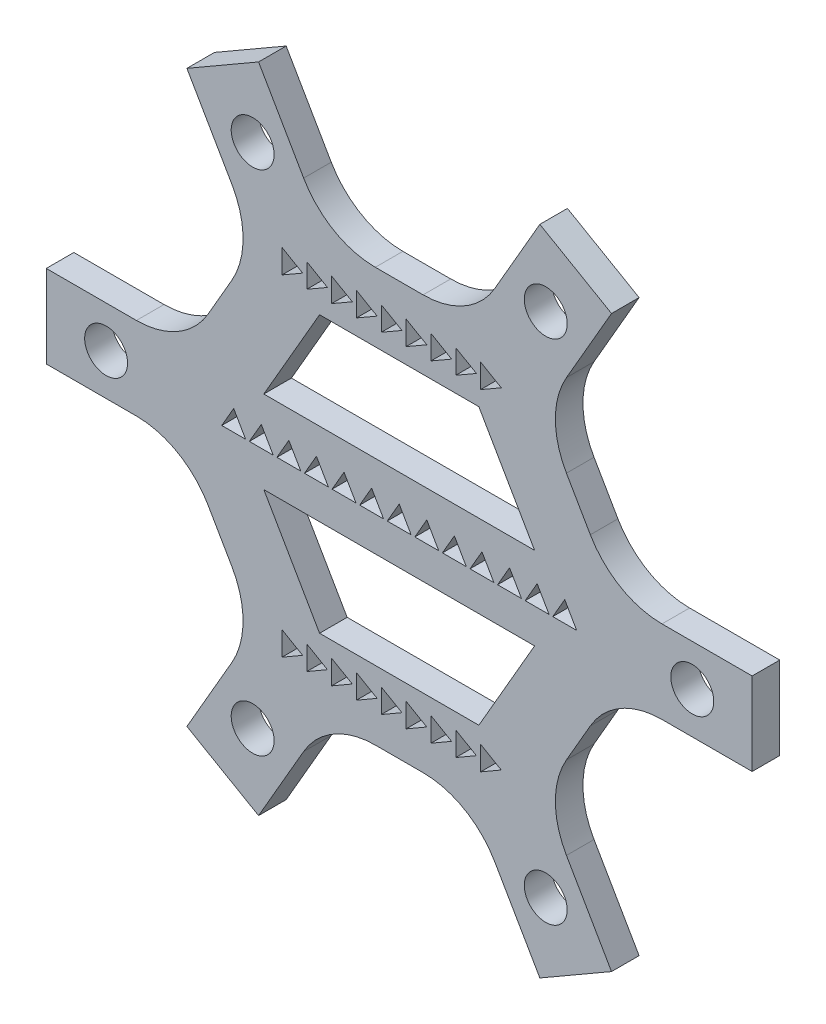
SolidWorks part; units mm, degrees
ref_plane "Front Plane" through (0, 0, 0) normal (0, 0, 1) x (1, 0, 0)
ref_plane "Top Plane" through (0, 0, 0) normal (0, 1, 0) x (1, 0, 0)
ref_plane "Right Plane" through (0, 0, 0) normal (1, 0, 0) x (0, 0, -1)
sketch "Sketch1" plane through (0, 0, 0) normal (0, 0, 1) x (1, 0, 0)
  line L0 (-49.0748, 15) -> (49.0748, 15)
  line L1 (69.282, 30) -> (60.6218, 45)
  line L2 (8.6603, 75) -> (-8.6603, 75)
  line L3 (-60.6218, 45) -> (-69.282, 30)
  line L4 (-69.282, -30) -> (-60.6218, -45)
  line L5 (-8.6603, -75) -> (8.6603, -75)
  line L6 (60.6218, -45) -> (69.282, -30)
  line L7 (57.735, 0) -> (28.8675, 50)
  line L8 (28.8675, 50) -> (-28.8675, 50)
  line L9 (-28.8675, 50) -> (-57.735, 0)
  line L10 (-57.735, 0) -> (-28.8675, -50)
  line L11 (-28.8675, -50) -> (28.8675, -50)
  line L12 (28.8675, -50) -> (57.735, 0)
  line L13 (34.641, 90) -> (50.9808, 118.3013)
  line L14 (-49.0748, -15) -> (49.0748, -15)
  line L15 (60.6218, 75) -> (76.9615, 103.3013)
  line L16 (95.2628, 15) -> (127.9423, 15)
  line L17 (95.2628, -15) -> (127.9423, -15)
  line L18 (34.641, -90) -> (50.9808, -118.3013)
  line L19 (60.6218, -75) -> (76.9615, -103.3013)
  line L20 (-60.6218, -75) -> (-76.9615, -103.3013)
  line L21 (-34.641, -90) -> (-50.9808, -118.3013)
  line L22 (-34.641, 90) -> (-50.9808, 118.3013)
  line L23 (-60.6218, 75) -> (-76.9615, 103.3013)
  line L24 (-95.2628, -15) -> (-127.9423, -15)
  line L25 (-95.2628, 15) -> (-127.9423, 15)
  line L26 (50.9808, 118.3013) -> (76.9615, 103.3013)
  line L27 (127.9423, 15) -> (127.9423, -15)
  line L28 (76.9615, -103.3013) -> (50.9808, -118.3013)
  line L29 (-76.9615, 103.3013) -> (-50.9808, 118.3013)
  line L30 (-127.9423, 15) -> (-127.9423, -15)
  line L31 (-76.9615, -103.3013) -> (-50.9808, -118.3013)
  circle A0 centre (0, 0) radius 75 construction
  arc A7 (-69.282, -30) -> (-95.2628, -15) centre (-95.2628, -45) ccw
  arc A8 (-69.282, 30) -> (-95.2628, 15) centre (-95.2628, 45) cw
  arc A9 (-60.6218, -45) -> (-60.6218, -75) centre (-86.6025, -60) cw
  arc A10 (-8.6603, -75) -> (-34.641, -90) centre (-8.6603, -105) ccw
  arc A11 (69.282, 30) -> (95.2628, 15) centre (95.2628, 45) ccw
  arc A12 (60.6218, 45) -> (60.6218, 75) centre (86.6025, 60) cw
  arc A13 (8.6603, 75) -> (34.641, 90) centre (8.6603, 105) ccw
  arc A14 (69.282, -30) -> (95.2628, -15) centre (95.2628, -45) cw
  arc A15 (60.6218, -45) -> (60.6218, -75) centre (86.6025, -60) ccw
  arc A16 (8.6603, -75) -> (34.641, -90) centre (8.6603, -105) cw
  arc A17 (-8.6603, 75) -> (-34.641, 90) centre (-8.6603, 105) cw
  arc A18 (-60.6218, 45) -> (-60.6218, 75) centre (-86.6025, 60) ccw
  dimension "D1" = 30
  dimension "D2" = 30
  dimension "D3" = 30
  dimension "D4" = 30
  dimension "D5" = 30
extrude "Boss-Extrude2" add sketch "Sketch1" along normal blind 10 contours L10 L14 L12 L7 L0 L9 | A18 L3 A8 L25 L30 L24 A7 L4 A9 L20 L31 L21 A10 L5 A16 L18 L28 L19 A15 L6 A14 L17 L27 L16 A11 L1 A12 L15 L26 L13 A13 L2 A17 L22 L29 L23 L12 L11 L10 L9 L8 L7
sketch "Sketch2" plane through (0, 0, 0) normal (0, 0, 1) x (1, 0, 0)
  circle A0 centre (106.2412, 0) radius 8
  circle A1 centre (53.1206, -92.0076) radius 8
  circle A2 centre (-53.1206, -92.0076) radius 8
  circle A3 centre (-106.2412, 0) radius 8
  circle A4 centre (-53.1206, 92.0076) radius 8
  circle A5 centre (53.1206, 92.0076) radius 8
  point P15 (0, 0)
  dimension "D1" = 6
extrude "Cut-Extrude1" cut sketch "Sketch2" along normal blind 17
sketch "Sketch3" plane through (0, 0, 0) normal (0, 0, 1) x (1, 0, 0)
  line L0 (-45.6699, -2.5) -> (-50, 5)
  line L1 (-55.6699, -2.5) -> (-60, 5)
  line L2 (-60, 5) -> (-64.3301, -2.5)
  line L3 (-64.3301, -2.5) -> (-55.6699, -2.5)
  line L4 (-50, 5) -> (-54.3301, -2.5)
  line L5 (-54.3301, -2.5) -> (-45.6699, -2.5)
  line L6 (-35.6699, -2.5) -> (-40, 5)
  line L7 (-40, 5) -> (-44.3301, -2.5)
  line L8 (-44.3301, -2.5) -> (-35.6699, -2.5)
  line L9 (-25.6699, -2.5) -> (-30, 5)
  line L10 (-30, 5) -> (-34.3301, -2.5)
  line L11 (-34.3301, -2.5) -> (-25.6699, -2.5)
  line L12 (-15.6699, -2.5) -> (-20, 5)
  line L13 (-20, 5) -> (-24.3301, -2.5)
  line L14 (-24.3301, -2.5) -> (-15.6699, -2.5)
  line L15 (-5.6699, -2.5) -> (-10, 5)
  line L16 (-10, 5) -> (-14.3301, -2.5)
  line L17 (-14.3301, -2.5) -> (-5.6699, -2.5)
  line L18 (4.3301, -2.5) -> (0, 5)
  line L19 (0, 5) -> (-4.3301, -2.5)
  line L20 (-4.3301, -2.5) -> (4.3301, -2.5)
  line L21 (14.3301, -2.5) -> (10, 5)
  line L22 (10, 5) -> (5.6699, -2.5)
  line L23 (5.6699, -2.5) -> (14.3301, -2.5)
  line L24 (24.3301, -2.5) -> (20, 5)
  line L25 (20, 5) -> (15.6699, -2.5)
  line L26 (15.6699, -2.5) -> (24.3301, -2.5)
  line L27 (34.3301, -2.5) -> (30, 5)
  line L28 (30, 5) -> (25.6699, -2.5)
  line L29 (25.6699, -2.5) -> (34.3301, -2.5)
  line L30 (44.3301, -2.5) -> (40, 5)
  line L31 (40, 5) -> (35.6699, -2.5)
  line L32 (35.6699, -2.5) -> (44.3301, -2.5)
  line L33 (54.3301, -2.5) -> (50, 5)
  line L34 (50, 5) -> (45.6699, -2.5)
  line L35 (45.6699, -2.5) -> (54.3301, -2.5)
  line L36 (64.3301, -2.5) -> (60, 5)
  line L37 (60, 5) -> (55.6699, -2.5)
  line L38 (55.6699, -2.5) -> (64.3301, -2.5)
  line L39 (-26, 60) -> (-33.5, 64.3301)
  line L40 (-35, 60) -> (-42.5, 64.3301)
  line L41 (-42.5, 64.3301) -> (-42.5, 55.6699)
  line L42 (-42.5, 55.6699) -> (-35, 60)
  line L43 (-33.5, 64.3301) -> (-33.5, 55.6699)
  line L44 (-33.5, 55.6699) -> (-26, 60)
  line L45 (-17, 60) -> (-24.5, 64.3301)
  line L46 (-24.5, 64.3301) -> (-24.5, 55.6699)
  line L47 (-24.5, 55.6699) -> (-17, 60)
  line L48 (-8, 60) -> (-15.5, 64.3301)
  line L49 (-15.5, 64.3301) -> (-15.5, 55.6699)
  line L50 (-15.5, 55.6699) -> (-8, 60)
  line L51 (1, 60) -> (-6.5, 64.3301)
  line L52 (-6.5, 64.3301) -> (-6.5, 55.6699)
  line L53 (-6.5, 55.6699) -> (1, 60)
  line L54 (10, 60) -> (2.5, 64.3301)
  line L55 (2.5, 64.3301) -> (2.5, 55.6699)
  line L56 (2.5, 55.6699) -> (10, 60)
  line L57 (19, 60) -> (11.5, 64.3301)
  line L58 (11.5, 64.3301) -> (11.5, 55.6699)
  line L59 (11.5, 55.6699) -> (19, 60)
  line L60 (28, 60) -> (20.5, 64.3301)
  line L61 (20.5, 64.3301) -> (20.5, 55.6699)
  line L62 (20.5, 55.6699) -> (28, 60)
  line L63 (37, 60) -> (29.5, 64.3301)
  line L64 (29.5, 64.3301) -> (29.5, 55.6699)
  line L65 (29.5, 55.6699) -> (37, 60)
  line L67 (29.5, -55.6699) -> (37, -60)
  line L68 (29.5, -64.3301) -> (29.5, -55.6699)
  line L69 (37, -60) -> (29.5, -64.3301)
  line L70 (20.5, -55.6699) -> (28, -60)
  line L71 (20.5, -64.3301) -> (20.5, -55.6699)
  line L72 (28, -60) -> (20.5, -64.3301)
  line L73 (11.5, -55.6699) -> (19, -60)
  line L74 (11.5, -64.3301) -> (11.5, -55.6699)
  line L75 (19, -60) -> (11.5, -64.3301)
  line L76 (2.5, -55.6699) -> (10, -60)
  line L77 (2.5, -64.3301) -> (2.5, -55.6699)
  line L78 (10, -60) -> (2.5, -64.3301)
  line L79 (-6.5, -55.6699) -> (1, -60)
  line L80 (-6.5, -64.3301) -> (-6.5, -55.6699)
  line L81 (1, -60) -> (-6.5, -64.3301)
  line L82 (-15.5, -55.6699) -> (-8, -60)
  line L83 (-15.5, -64.3301) -> (-15.5, -55.6699)
  line L84 (-8, -60) -> (-15.5, -64.3301)
  line L85 (-24.5, -55.6699) -> (-17, -60)
  line L86 (-24.5, -64.3301) -> (-24.5, -55.6699)
  line L87 (-17, -60) -> (-24.5, -64.3301)
  line L88 (-33.5, -55.6699) -> (-26, -60)
  line L89 (-33.5, -64.3301) -> (-33.5, -55.6699)
  line L90 (-42.5, -55.6699) -> (-35, -60)
  line L91 (-42.5, -64.3301) -> (-42.5, -55.6699)
  line L92 (-35, -60) -> (-42.5, -64.3301)
  line L93 (-26, -60) -> (-33.5, -64.3301)
  circle A0 centre (-60, 0) radius 2.5 construction
  circle A1 centre (-40, 60) radius 2.5 construction
  circle A2 centre (-40, -60) radius 2.5 construction
  dimension "D1" = 13
  dimension "D2" = 9
extrude "Cut-Extrude2" cut sketch "Sketch3" along normal blind 20
sketch "Sketch4" plane through (0, 0, 0) normal (0, 0, 1) x (1, 0, 0)
  circle A0 centre (106.2412, 0) radius 8
  circle A1 centre (106.2412, 0) radius 2.8
  circle A2 centre (53.1206, -92.0076) radius 2.8
  circle A3 centre (53.1206, -92.0076) radius 8
  circle A4 centre (-53.1206, -92.0076) radius 2.8
  circle A5 centre (-53.1206, -92.0076) radius 8
  circle A6 centre (-106.2412, 0) radius 2.8
  circle A7 centre (-106.2412, 0) radius 8
  circle A8 centre (-53.1206, 92.0076) radius 2.8
  circle A9 centre (-53.1206, 92.0076) radius 8
  circle A10 centre (53.1206, 92.0076) radius 2.8
  circle A11 centre (53.1206, 92.0076) radius 8
  point P22 (0, 0)
  dimension "D1" = 6
extrude "Boss-Extrude3" add sketch "Sketch4" along normal blind 10
sketch "Sketch5" plane through (0, 0, 0) normal (0, 0, 1) x (1, 0, 0)
  circle A0 centre (106.2412, 0) radius 7.78
  circle A1 centre (53.1206, -92.0076) radius 7.78
  circle A2 centre (-53.1206, -92.0076) radius 7.78
  circle A3 centre (-106.2412, 0) radius 7.78
  circle A4 centre (-53.1206, 92.0076) radius 7.78
  circle A5 centre (53.1206, 92.0076) radius 7.78
  point P16 (0, 0)
  dimension "D1" = 6
extrude "Cut-Extrude3" cut sketch "Sketch5" along normal blind 19
